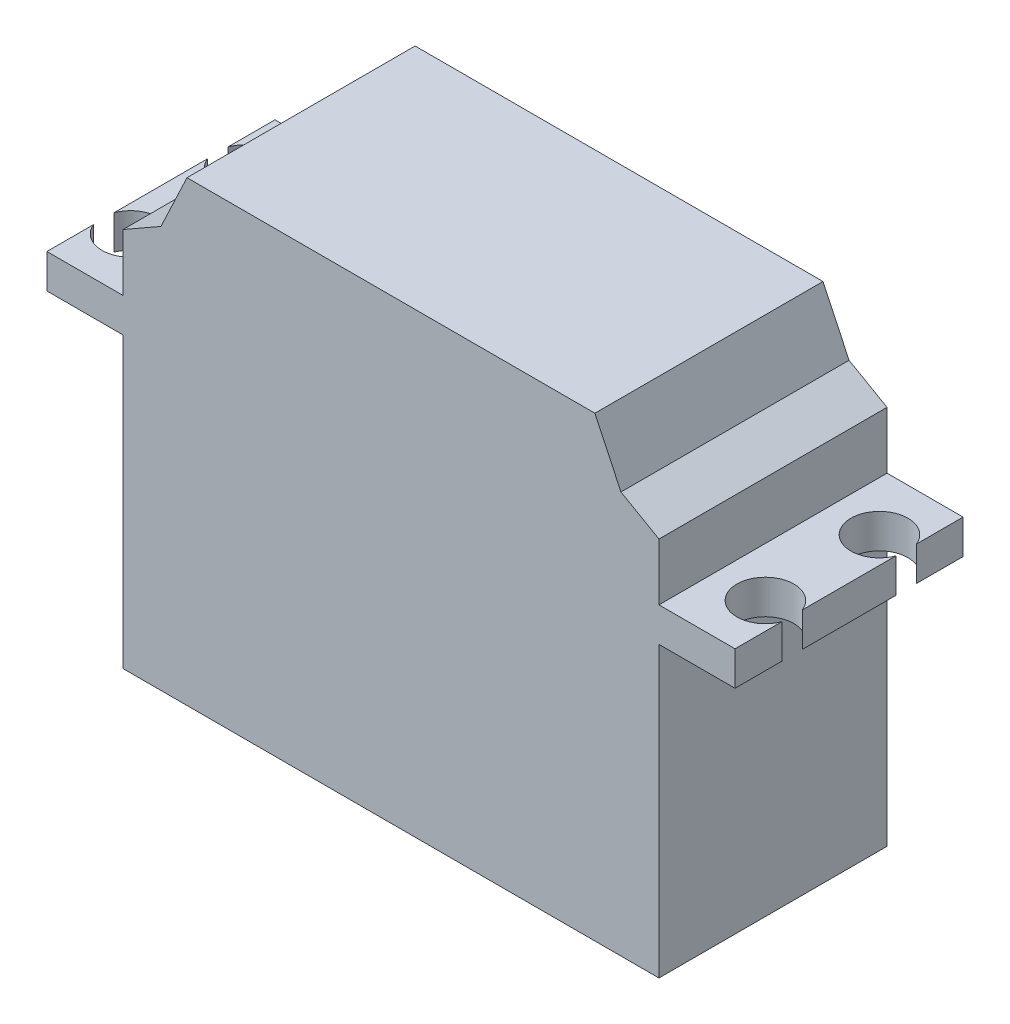
SolidWorks part; units mm, degrees
ref_plane "Front Plane" through (0, 0, 0) normal (0, 0, 1) x (1, 0, 0)
ref_plane "Top Plane" through (0, 0, 0) normal (0, 1, 0) x (1, 0, 0)
ref_plane "Right Plane" through (0, 0, 0) normal (1, 0, 0) x (0, 0, -1)
sketch "Sketch1" plane through (0, 0, 0) normal (0, 1, 0) x (1, 0, 0)
  line L1 (-17.907, 7.62) -> (17.907, 7.62)
  line L2 (-17.907, 7.62) -> (-17.907, -7.62)
  line L3 (-17.907, -7.62) -> (17.907, -7.62)
  line L4 (17.907, 7.62) -> (17.907, -7.62)
  line L5 (-17.907, 7.62) -> (17.907, -7.62) construction
  line L6 (-17.907, -7.62) -> (17.907, 7.62) construction
  point P0 (0, 0)
  dimension "D1" = 15.24
  dimension "D2" = 35.814
extrude "Boss-Extrude1" add sketch "Sketch1" along normal blind 25.4
sketch "Sketch2" plane through (0, 0, 7.62) normal (0, 0, 1) x (1, 0, 0)
  line L0 (-9.017, 30.48) -> (9.017, 30.48) construction
  line L1 (-17.907, 25.4) -> (17.907, 25.4) construction
  line L2 (-17.907, 25.4) -> (-8.89, 25.4) construction
  line L3 (0, 25.4) -> (0, 0) construction
  line L4 (17.907, 25.4) -> (8.89, 25.4) construction
  line L5 (-9.017, 30.48) -> (9.017, 30.48)
  line L6 (-17.907, 25.4) -> (-9.017, 30.48)
  line L7 (9.017, 30.48) -> (17.907, 25.4)
  line L8 (-17.907, 25.4) -> (17.907, 25.4)
  dimension "D1" = 5.08
  dimension "D3" = 8.89
  dimension "D4" = 8.89
extrude "Boss-Extrude2" add sketch "Sketch2" against normal up to surface (15.24 mm away) up to face at (0, 12.7, -7.62)
sketch "Sketch3" plane through (0, 0, 7.62) normal (0, 0, 1) x (1, 0, 0)
  line L0 (-15.367, 26.8514) -> (-13.6269, 30.5401)
  line L1 (-9.017, 30.48) -> (-17.907, 25.4) construction
  line L2 (-13.6269, 30.5401) -> (13.6269, 30.5401)
  line L4 (0, 30.48) -> (0, 30.5401) construction
  line L6 (-15.367, 26.8514) -> (-9.017, 30.48)
  line L7 (-9.017, 30.48) -> (9.017, 30.48)
  line L9 (15.367, 26.8514) -> (9.017, 30.48)
  line L10 (15.367, 26.8514) -> (13.6269, 30.5401)
  dimension "D2" = 35
  dimension "D4" = 2.54
extrude "Boss-Extrude3" add sketch "Sketch3" against normal up to surface (15.24 mm away) up to face at (0, 18.6267, -7.62)
sketch "Sketch4" plane through (0, 0, 7.62) normal (0, 0, 1) x (1, 0, 0)
  line L0 (-17.907, 25.4) -> (-17.907, 21.59) construction
  line L1 (-17.907, 25.4) -> (-17.907, 0) construction
  line L2 (-22.987, 19.304) -> (-22.987, 21.59)
  line L3 (-17.907, 21.59) -> (-17.907, 19.304)
  line L4 (-17.907, 19.304) -> (-22.987, 19.304)
  line L5 (-22.987, 21.59) -> (-17.907, 21.59)
  line L6 (0, 30.5401) -> (0, 0) construction
  line L7 (13.6269, 30.5401) -> (-13.6269, 30.5401) construction
  line L8 (22.987, 19.304) -> (22.987, 21.59)
  line L9 (17.907, 19.304) -> (22.987, 19.304)
  line L10 (17.907, 21.59) -> (17.907, 19.304)
  line L11 (22.987, 21.59) -> (17.907, 21.59)
  dimension "D1" = 3.81
  dimension "D2" = 5.08
  dimension "D3" = 2.286
extrude "Boss-Extrude4" add sketch "Sketch4" against normal up to surface (15.24 mm away) up to face at (0, 20.6979, -7.62)
sketch "Sketch5" plane through (0, 21.59, 0) normal (0, 1, 0) x (1, 0, 0)
  line L0 (-17.907, 0) -> (-22.987, 0) construction
  line L1 (-17.907, 7.62) -> (-17.907, -7.62) construction
  line L2 (-22.987, 7.62) -> (-22.987, -7.62) construction
  line L3 (-17.907, 7.62) -> (-17.907, -7.62) construction
  line L4 (-22.987, 7.62) -> (-22.987, 0) construction
  line L5 (-22.987, 3.81) -> (-17.907, 3.81) construction
  line L6 (0, 7.62) -> (0, -7.62) construction
  line L7 (-13.6269, 7.62) -> (13.6269, 7.62) construction
  line L8 (13.6269, -7.62) -> (-13.6269, -7.62) construction
  circle A0 centre (-21.209, 3.81) radius 1.905
  circle A1 centre (-21.209, -3.81) radius 1.905
  circle A2 centre (21.209, -3.81) radius 1.905
  circle A3 centre (21.209, 3.81) radius 1.905
  point P16 (-20.447, 3.81)
  dimension "D1" = 3.81
  dimension "D2" = 3.302
extrude "Cut-Extrude1" cut sketch "Sketch5" against normal up to surface (2.286 mm away) up to face at (-20.447, 19.304, 0)
